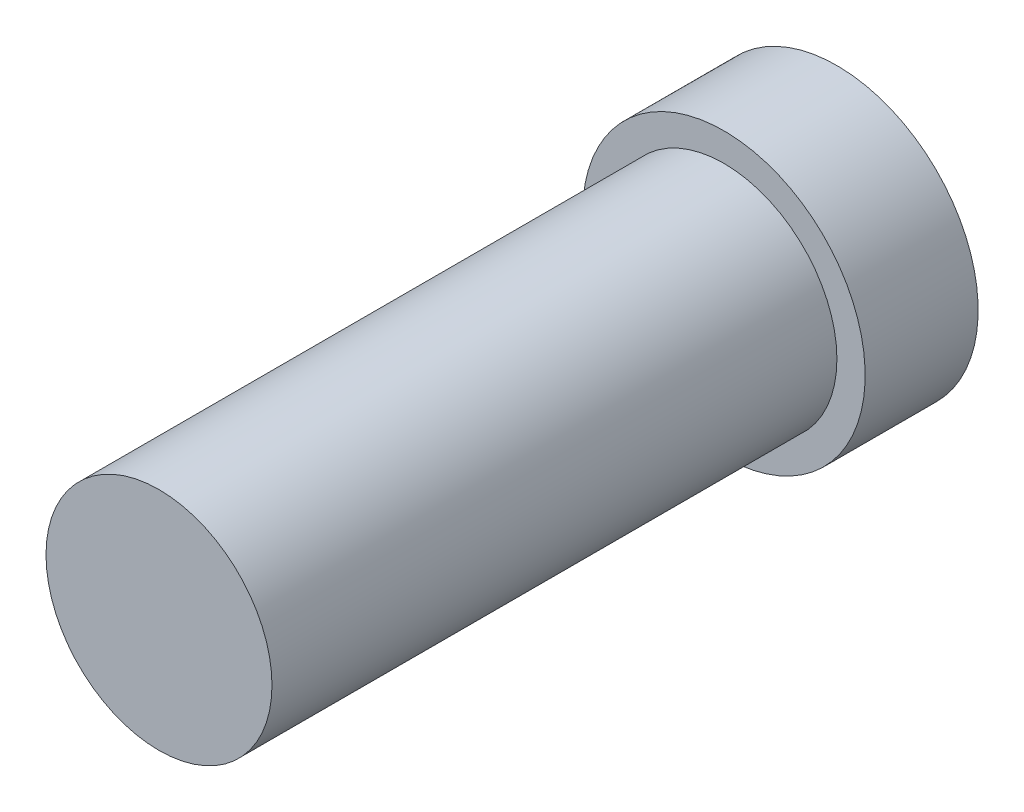
SolidWorks part; units mm, degrees
ref_plane "Front" through (0, 0, 0) normal (0, 0, 1) x (1, 0, 0)
ref_plane "Top" through (0, 0, 0) normal (0, 1, 0) x (1, 0, 0)
ref_plane "Right" through (0, 0, 0) normal (1, 0, 0) x (0, 0, -1)
sketch "Çizim1" plane through (0, 0, 0) normal (0, 0, 1) x (1, 0, 0)
  circle A0 centre (0, 0) radius 2
extrude "Yükseklik-Ekstrüzyon1" add sketch "Çizim1" along normal blind 10
sketch "Çizim2" plane through (0, 0, 0) normal (0, 0, -1) x (-1, 0, 0)
  circle A0 centre (0, 0) radius 2.5
extrude "Yükseklik-Ekstrüzyon2" add sketch "Çizim2" along normal blind 2
